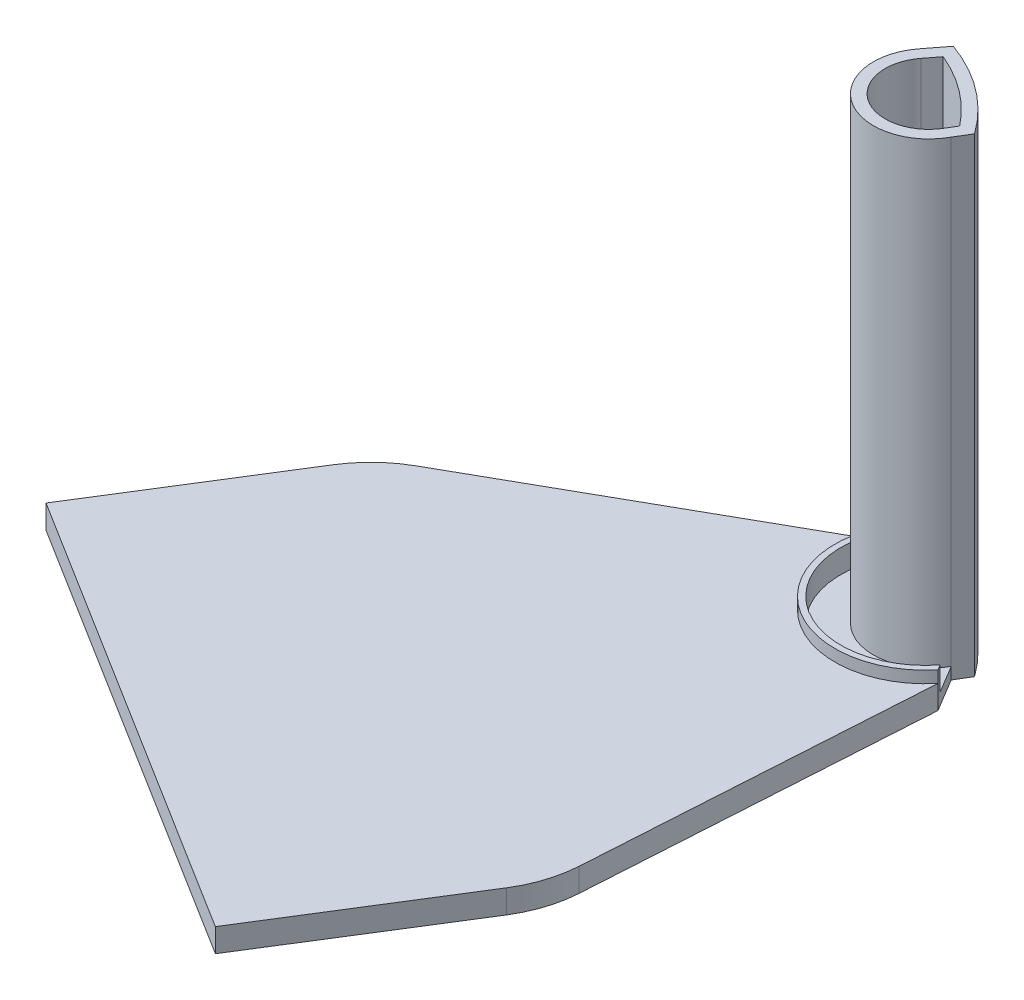
SolidWorks part; units mm, degrees
ref_plane "Alzado" through (0, 0, 0) normal (0, 0, 1) x (1, 0, 0)
ref_plane "Planta" through (0, 0, 0) normal (0, 1, 0) x (1, 0, 0)
ref_plane "Vista lateral" through (0, 0, 0) normal (1, 0, 0) x (0, 0, -1)
sketch "Croquis3" plane through (0, 62.3853, 0) normal (0, 1, 0) x (1, 0, 0)
  line L0 (-8.0359, 0.8886) -> (-4.6602, 0.7384)
  line L1 (3.2253, -4.3817) -> (4.9174, -7.2023)
  arc A3 (-8.0359, 0.8886) -> (4.9174, -7.2023) centre (-1.0355, -2.3184) ccw
  arc A4 (-4.6602, 0.7384) -> (3.2253, -4.3817) centre (-0.9235, -2.1391) ccw
extrude "Saliente-Extruir3" add sketch "Croquis3" along normal blind 1
sketch "Croquis1" plane through (0, 62.3853, 0) normal (0, 1, 0) x (1, 0, 0)
  line L2 (-4.6602, 0.7384) -> (-3.3811, 2.3993)
  line L3 (3.2253, -4.3817) -> (3.9762, -3.1511)
  line L5 (-3.8679, 0.1282) -> (-3.0435, 1.1987)
  line L6 (2.3572, -3.8845) -> (2.7699, -3.2081)
  arc A5 (-4.6602, 0.7384) -> (3.2253, -4.3817) centre (-0.9235, -2.1391) ccw construction
  arc A6 (-4.6602, 0.7384) -> (3.2253, -4.3817) centre (-0.9235, -2.1391) ccw
  arc A9 (2.7699, -3.2081) -> (-3.0435, 1.1987) centre (-8.5312, -12.0786) ccw
  arc A10 (-3.8679, 0.1282) -> (2.3572, -3.8845) centre (-0.9235, -2.1391) ccw
  arc A14 (3.9762, -3.1511) -> (-3.3811, 2.3993) centre (-8.5312, -12.0786) ccw
  dimension "D1" = 1
sketch "Croquis4" plane through (0, 63.3853, 0) normal (0, 1, 0) x (1, 0, 0)
  line L6 (-4.6602, 0.7384) -> (-8.0359, 0.8886) construction
  line L7 (4.9174, -7.2023) -> (3.2253, -4.3817) construction
  line L8 (4.9174, -7.2023) -> (4.643, -6.745)
  line L9 (-7.4938, 0.8645) -> (-8.0359, 0.8886)
  arc A1 (-8.0359, 0.8886) -> (4.9174, -7.2023) centre (-1.0355, -2.3184) ccw
  arc A3 (-8.0359, 0.8886) -> (4.9174, -7.2023) centre (-1.0355, -2.3184) ccw construction
  arc A4 (-7.4938, 0.8645) -> (4.643, -6.745) centre (-1.0355, -2.3184) ccw
  arc A5 (-7.5813, 0.6803) -> (4.643, -6.745) centre (-1.0355, -2.3184) ccw construction
  arc A6 (-8.0359, 0.8886) -> (5.0373, -7.0524) centre (-1.0355, -2.3184) ccw construction
  dimension "D1" = 0.5
extrude "Saliente-Extruir4" add sketch "Croquis4" along normal blind 2
extrude "Saliente-Extruir5" add sketch "Croquis1" along normal blind 40
sketch "Croquis8" plane through (0, 62.3853, 0) normal (0, -1, 0) x (1, 0, 0)
  line L1 (1.6217, 40.6146) -> (-7.9036, 55.8584)
  line L2 (-7.9036, 55.8584) -> (-46.3202, 31.853)
  line L3 (-46.3202, 31.853) -> (-36.9131, 16.7986)
  line L4 (-33.3457, 13.3879) -> (-8.0359, -0.8886)
  line L5 (3.1218, 35.939) -> (4.9174, 7.2023)
  circle A0 centre (-10.4107, 42.2642) radius 7.65
  circle A1 centre (-33.0027, 28.1471) radius 7.65
  arc A2 (3.1218, 35.939) -> (1.6217, 40.6146) centre (-6.8587, 35.3154) ccw
  arc A3 (-33.3457, 13.3879) -> (-36.9131, 16.7986) centre (-28.4327, 22.0978) cw
  arc M11 (4.9174, 7.2023) -> (-8.0359, -0.8886) centre (-1.0355, 2.3184) ccw
  dimension "D1" = 15.3
  dimension "D2" = 15.3
  dimension "D4" = 10
  dimension "D3" = 26.64
  dimension "D5" = 45.3
  dimension "D6" = 9.33
extrude "Saliente-Extruir6" add sketch "Croquis8" against normal blind 2 contours A3 L4 L5 A2 L1 L2 L3 A1 A0 M11 | A0
